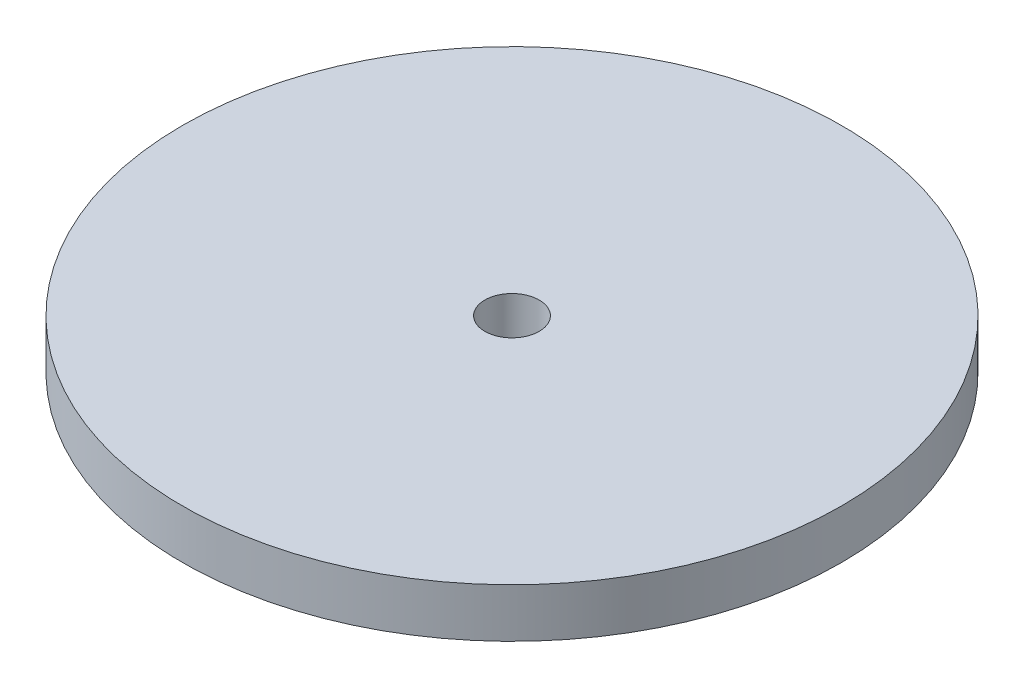
SolidWorks part; units mm, degrees
ref_plane "Front Plane" through (0, 0, 0) normal (0, 0, 1) x (1, 0, 0)
ref_plane "Top Plane" through (0, 0, 0) normal (0, 1, 0) x (1, 0, 0)
ref_plane "Right Plane" through (0, 0, 0) normal (1, 0, 0) x (0, 0, -1)
sketch "Sketch1" plane through (0, 0, 0) normal (0, 0, 1) x (1, 0, 0)
  line L0 (1.7853, 9.3213) -> (1.7853, 6.3458)
  line L1 (1.7853, 6.3458) -> (20.1353, 6.3458)
  line L2 (20.1353, 6.3458) -> (20.1353, 9.3213)
  line L3 (20.1353, 9.3213) -> (1.7853, 9.3213)
  line L4 (0.1353, 9.3213) -> (0.1353, 6.3458) construction
  dimension "D1" = 20
  dimension "D2" = 1.65
revolve "Revolve1" add sketch "Sketch1" angle 360 about L4
